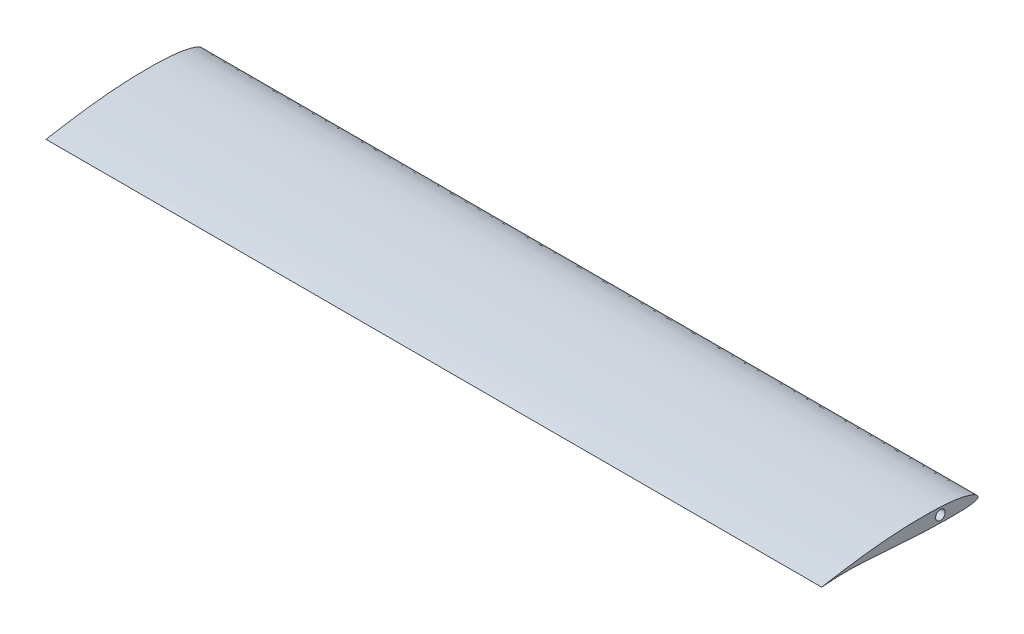
SolidWorks part; units mm, degrees
ref_plane "Piano frontale" through (0, 0, 0) normal (0, 0, 1) x (1, 0, 0)
ref_plane "Piano superiore" through (0, 0, 0) normal (0, 1, 0) x (1, 0, 0)
ref_plane "Piano destro" through (0, 0, 0) normal (1, 0, 0) x (0, 0, -1)
curve "Curva1"
  spline degree 3 poles (0, 0.1793, 258.2164) (0, -0.0551, 260.4444) (0, 0.2561, 258.2615) (0, 0.575, 256.5103) (0, 1.2957, 252.327) (0, 2.1829, 247.2563) (0, 3.3091, 240.6179) (0, 4.465, 232.9362) (0, 5.9605, 224.1828) (0, 7.4168, 214.5525) (0, 8.9777, 204.0096) (0, 10.5209, 192.7665) (0, 12.0113, 180.9486) (0, 13.3969, 168.679) (0, 14.6217, 156.0753) (0, 15.6544, 143.2535) (0, 16.4586, 130.3241) (0, 17.0387, 117.4044) (0, 17.3958, 104.6209) (0, 17.5393, 92.1096) (0, 17.4637, 80.0086) (0, 17.1538, 68.4492) (0, 16.5993, 57.5462) (0, 15.7658, 47.3959) (0, 14.6617, 38.0717) (0, 13.2999, 29.6371) (0, 11.7353, 22.1507) (0, 10.027, 15.6779) (0, 8.2301, 10.2762) (0, 6.3629, 6.0007) (0, 4.4079, 2.838) (0, 2.3979, 0.8451) (0, 0.8244, 0.0324) (0, -0.4269, -0.0222) (0, -1.78, 0.5147) (0, -2.9804, 2.7303) (0, -4.2021, 5.9256) (0, -5.1259, 10.4748) (0, -5.8213, 16.2513) (0, -6.2527, 23.3087) (0, -6.5157, 31.5764) (0, -6.6366, 40.9731) (0, -6.6096, 51.3747) (0, -6.4672, 62.6551) (0, -6.1856, 74.6739) (0, -5.7583, 87.2985) (0, -5.1361, 100.4079) (0, -4.3189, 113.9009) (0, -3.3484, 127.6778) (0, -2.2786, 141.6234) (0, -1.1939, 155.6004) (0, -0.1666, 169.4487) (0, 0.7343, 182.9918) (0, 1.4452, 196.0399) (0, 1.9065, 208.386) (0, 2.0463, 219.7911) (0, 1.8961, 230.0315) (0, 1.5572, 238.8676) (0, 1.1171, 246.2787) (0, 0.7131, 251.877) (0, 0.321, 256.3788) (0, 0.1793, 258.2164) (0, -0.0551, 260.4444) (0, 0.2561, 258.2615) knots -0.014202 -0.006329 -0.001589 0 0.001576 0.006211 0.01368 0.023764 0.036307 0.051658 0.068045 0.086769 0.107053 0.128647 0.151303 0.174786 0.19886 0.223309 0.247929 0.272522 0.296848 0.320648 0.343669 0.365658 0.3864 0.405741 0.423561 0.439779 0.454311 0.467034 0.477831 0.486643 0.493542 0.498786 0.50271 0.50309 0.505896 0.510322 0.516831 0.525521 0.536535 0.549945 0.565696 0.583577 0.603379 0.624844 0.647727 0.671743 0.696673 0.722357 0.748609 0.77521 0.801891 0.828329 0.854175 0.879074 0.902636 0.924421 0.943939 0.960827 0.974827 0.985798 0.993671 0.998411 1 1.001576 1.006211 1.01368 periodic
sketch "Schizzo1" plane through (0, 0, 0) normal (1, 0, 0) x (0, 0, -1)
  spline S0 degree 3 poles (-258.2615, 0.2561) (-260.4444, -0.0551) (-258.2164, 0.1793) (-256.3788, 0.321) (-251.877, 0.7131) (-246.2787, 1.1171) (-238.8676, 1.5572) (-230.0315, 1.8961) (-219.7911, 2.0463) (-208.386, 1.9065) (-196.0399, 1.4452) (-182.9918, 0.7343) (-169.4487, -0.1666) (-155.6004, -1.1939) (-141.6234, -2.2786) (-127.6778, -3.3484) (-113.9009, -4.3189) (-100.4079, -5.1361) (-87.2985, -5.7583) (-74.6739, -6.1856) (-62.6551, -6.4672) (-51.3747, -6.6096) (-40.9731, -6.6366) (-31.5764, -6.5157) (-23.3087, -6.2527) (-16.2513, -5.8213) (-10.4748, -5.1259) (-5.9256, -4.2021) (-2.7303, -2.9804) (-0.5147, -1.78) (0.0222, -0.4269) (-0.0324, 0.8244) (-0.8451, 2.3979) (-2.838, 4.4079) (-6.0007, 6.3629) (-10.2762, 8.2301) (-15.6779, 10.027) (-22.1507, 11.7353) (-29.6371, 13.2999) (-38.0717, 14.6617) (-47.3959, 15.7658) (-57.5462, 16.5993) (-68.4492, 17.1538) (-80.0086, 17.4637) (-92.1096, 17.5393) (-104.6209, 17.3958) (-117.4044, 17.0387) (-130.3241, 16.4586) (-143.2535, 15.6544) (-156.0753, 14.6217) (-168.679, 13.3969) (-180.9486, 12.0113) (-192.7665, 10.5209) (-204.0096, 8.9777) (-214.5525, 7.4168) (-224.1828, 5.9605) (-232.9362, 4.465) (-240.6179, 3.3091) (-247.2563, 2.1829) (-252.327, 1.2957) (-256.5103, 0.575) (-258.2615, 0.2561) (-260.4444, -0.0551) (-258.2164, 0.1793) knots -0.01368 -0.006211 -0.001576 0 0.001589 0.006329 0.014202 0.025173 0.039173 0.056061 0.075579 0.097364 0.120926 0.145825 0.171671 0.198109 0.22479 0.251391 0.277643 0.303327 0.328257 0.352273 0.375156 0.396621 0.416423 0.434304 0.450055 0.463465 0.474479 0.483169 0.489678 0.494104 0.49691 0.49729 0.501214 0.506458 0.513357 0.522169 0.532966 0.545689 0.560221 0.576439 0.594259 0.6136 0.634342 0.656331 0.679352 0.703152 0.727478 0.752071 0.776691 0.80114 0.825214 0.848697 0.871353 0.892947 0.913231 0.931955 0.948342 0.963693 0.976236 0.98632 0.993789 0.998424 1 1.001589 1.006329 1.014202 only from (-260, 0) to (-260, 0) construction
  spline S1 degree 3 poles (-258.2615, 0.2561) (-260.4444, -0.0551) (-258.2164, 0.1793) (-256.3788, 0.321) (-251.877, 0.7131) (-246.2787, 1.1171) (-238.8676, 1.5572) (-230.0315, 1.8961) (-219.7911, 2.0463) (-208.386, 1.9065) (-196.0399, 1.4452) (-182.9918, 0.7343) (-169.4487, -0.1666) (-155.6004, -1.1939) (-141.6234, -2.2786) (-127.6778, -3.3484) (-113.9009, -4.3189) (-100.4079, -5.1361) (-87.2985, -5.7583) (-74.6739, -6.1856) (-62.6551, -6.4672) (-51.3747, -6.6096) (-40.9731, -6.6366) (-31.5764, -6.5157) (-23.3087, -6.2527) (-16.2513, -5.8213) (-10.4748, -5.1259) (-5.9256, -4.2021) (-2.7303, -2.9804) (-0.5147, -1.78) (0.0222, -0.4269) (-0.0324, 0.8244) (-0.8451, 2.3979) (-2.838, 4.4079) (-6.0007, 6.3629) (-10.2762, 8.2301) (-15.6779, 10.027) (-22.1507, 11.7353) (-29.6371, 13.2999) (-38.0717, 14.6617) (-47.3959, 15.7658) (-57.5462, 16.5993) (-68.4492, 17.1538) (-80.0086, 17.4637) (-92.1096, 17.5393) (-104.6209, 17.3958) (-117.4044, 17.0387) (-130.3241, 16.4586) (-143.2535, 15.6544) (-156.0753, 14.6217) (-168.679, 13.3969) (-180.9486, 12.0113) (-192.7665, 10.5209) (-204.0096, 8.9777) (-214.5525, 7.4168) (-224.1828, 5.9605) (-232.9362, 4.465) (-240.6179, 3.3091) (-247.2563, 2.1829) (-252.327, 1.2957) (-256.5103, 0.575) (-258.2615, 0.2561) (-260.4444, -0.0551) (-258.2164, 0.1793) knots -0.01368 -0.006211 -0.001576 0 0.001589 0.006329 0.014202 0.025173 0.039173 0.056061 0.075579 0.097364 0.120926 0.145825 0.171671 0.198109 0.22479 0.251391 0.277643 0.303327 0.328257 0.352273 0.375156 0.396621 0.416423 0.434304 0.450055 0.463465 0.474479 0.483169 0.489678 0.494104 0.49691 0.49729 0.501214 0.506458 0.513357 0.522169 0.532966 0.545689 0.560221 0.576439 0.594259 0.6136 0.634342 0.656331 0.679352 0.703152 0.727478 0.752071 0.776691 0.80114 0.825214 0.848697 0.871353 0.892947 0.913231 0.931955 0.948342 0.963693 0.976236 0.98632 0.993789 0.998424 1 1.001589 1.006329 1.014202 only from (-260, 0) to (-260, 0)
extrude "Estrusione-Estrusione1" add sketch "Schizzo1" along normal blind 1290
sketch "Schizzo2" plane through (1290, 0, 0) normal (1, 0, 0) x (0, 0, -1)
  line L0 (-260, 0) -> (0, 0) construction
  line L1 (-62.5, 16.8382) -> (-62.5, -6.4489) construction
  circle A0 centre (-62.5, 5.1947) radius 8
  spline S0 degree 3 poles (-258.2615, 0.2561) (-260.4444, -0.0551) (-258.2164, 0.1793) (-256.3788, 0.321) (-251.877, 0.7131) (-246.2787, 1.1171) (-238.8676, 1.5572) (-230.0315, 1.8961) (-219.7911, 2.0463) (-208.386, 1.9065) (-196.0399, 1.4452) (-182.9918, 0.7343) (-169.4487, -0.1666) (-155.6004, -1.1939) (-141.6234, -2.2786) (-127.6778, -3.3484) (-113.9009, -4.3189) (-100.4079, -5.1361) (-87.2985, -5.7583) (-74.6739, -6.1856) (-62.6551, -6.4672) (-51.3747, -6.6096) (-40.9731, -6.6366) (-31.5764, -6.5157) (-23.3087, -6.2527) (-16.2513, -5.8213) (-10.4748, -5.1259) (-5.9256, -4.2021) (-2.7303, -2.9804) (-0.5147, -1.78) (0.0222, -0.4269) (-0.0324, 0.8244) (-0.8451, 2.3979) (-2.838, 4.4079) (-6.0007, 6.3629) (-10.2762, 8.2301) (-15.6779, 10.027) (-22.1507, 11.7353) (-29.6371, 13.2999) (-38.0717, 14.6617) (-47.3959, 15.7658) (-57.5462, 16.5993) (-68.4492, 17.1538) (-80.0086, 17.4637) (-92.1096, 17.5393) (-104.6209, 17.3958) (-117.4044, 17.0387) (-130.3241, 16.4586) (-143.2535, 15.6544) (-156.0753, 14.6217) (-168.679, 13.3969) (-180.9486, 12.0113) (-192.7665, 10.5209) (-204.0096, 8.9777) (-214.5525, 7.4168) (-224.1828, 5.9605) (-232.9362, 4.465) (-240.6179, 3.3091) (-247.2563, 2.1829) (-252.327, 1.2957) (-256.5103, 0.575) (-258.2615, 0.2561) (-260.4444, -0.0551) (-258.2164, 0.1793) knots -0.01368 -0.006211 -0.001576 0 0.001589 0.006329 0.014202 0.025173 0.039173 0.056061 0.075579 0.097364 0.120926 0.145825 0.171671 0.198109 0.22479 0.251391 0.277643 0.303327 0.328257 0.352273 0.375156 0.396621 0.416423 0.434304 0.450055 0.463465 0.474479 0.483169 0.489678 0.494104 0.49691 0.49729 0.501214 0.506458 0.513357 0.522169 0.532966 0.545689 0.560221 0.576439 0.594259 0.6136 0.634342 0.656331 0.679352 0.703152 0.727478 0.752071 0.776691 0.80114 0.825214 0.848697 0.871353 0.892947 0.913231 0.931955 0.948342 0.963693 0.976236 0.98632 0.993789 0.998424 1 1.001589 1.006329 1.014202 only from (-260, 0) to (-260, 0) construction
  dimension "D2" = 16
  dimension "D1" = 62.5
extrude "Taglio-Estrusione1" cut sketch "Schizzo2" against normal through all
